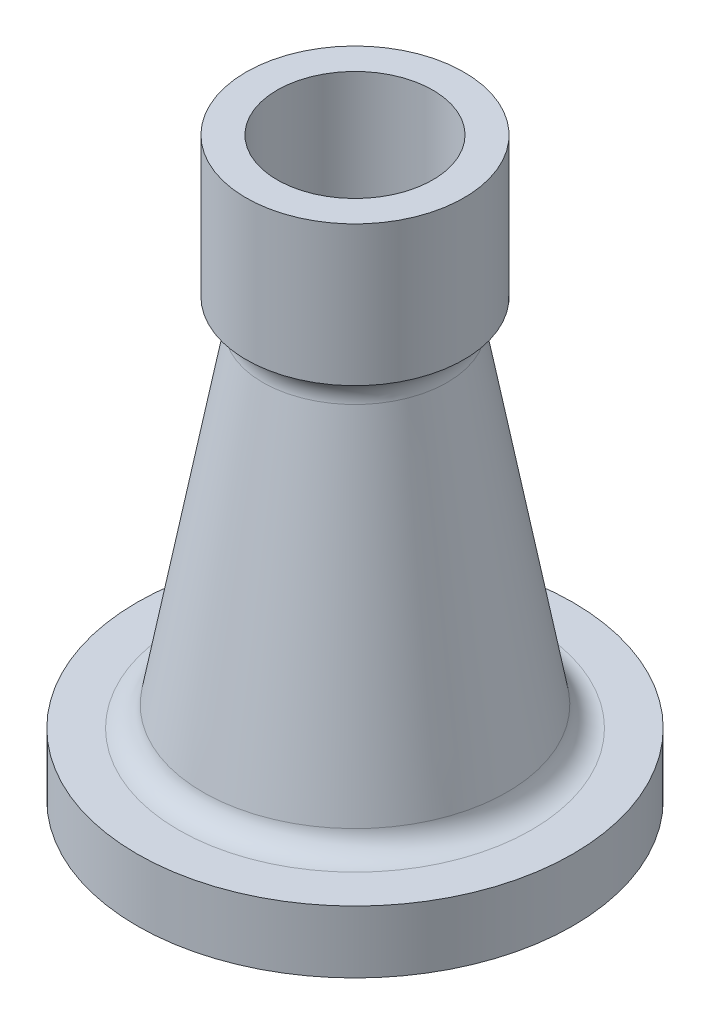
SolidWorks part; units mm, degrees
material "Gray Cast Iron"
ref_plane "Front Plane" through (0, 0, 0) normal (0, 0, 1) x (1, 0, 0)
ref_plane "Top Plane" through (0, 0, 0) normal (0, 1, 0) x (1, 0, 0)
ref_plane "Right Plane" through (0, 0, 0) normal (1, 0, 0) x (0, 0, -1)
sketch "Sketch3" plane through (0, 0, 0) normal (0, 0, 1) x (1, 0, 0)
  line L0 (0, 92.5) -> (0, -92.5) construction
  line L1 (25, 92.5) -> (25, 8.2117)
  line L2 (35, 92.5) -> (35, 47.5)
  line L3 (50, -92.5) -> (50, -92)
  line L4 (70, -92.5) -> (70, -72.5)
  line L5 (50, -92.5) -> (70, -92.5)
  line L6 (70, -72.5) -> (56.6638, -72.5)
  line L7 (48.7956, -65.946) -> (29.6109, 38.4479)
  line L8 (25, 8.2117) -> (42.9567, -89.5)
  line L9 (47.5, -89.5) -> (42.9567, -89.5)
  line L10 (25, 92.5) -> (35, 92.5)
  arc A0 (35, 47.5) -> (29.6109, 38.4479) centre (37.4791, 39.8938) ccw
  arc A1 (56.6638, -72.5) -> (48.7956, -65.946) centre (56.6638, -64.5) cw
  arc A2 (50, -92) -> (47.5, -89.5) centre (47.5, -92) ccw
  point P16 (50, -72.5)
  point P20 (50, -89.5)
  dimension "D10" = 8
  dimension "D11" = 8
  dimension "D12" = 2.5
  dimension "D1" = 185
  dimension "D2" = 20
  dimension "D3" = 45
  dimension "D4" = 70
  dimension "D5" = 50
  dimension "D6" = 140
  dimension "D7" = 100
  dimension "D8" = 3
  dimension "D9" = 10
  dimension "D13" = 10.413
revolve "Revolve1" add sketch "Sketch3" angle 360 about L0
